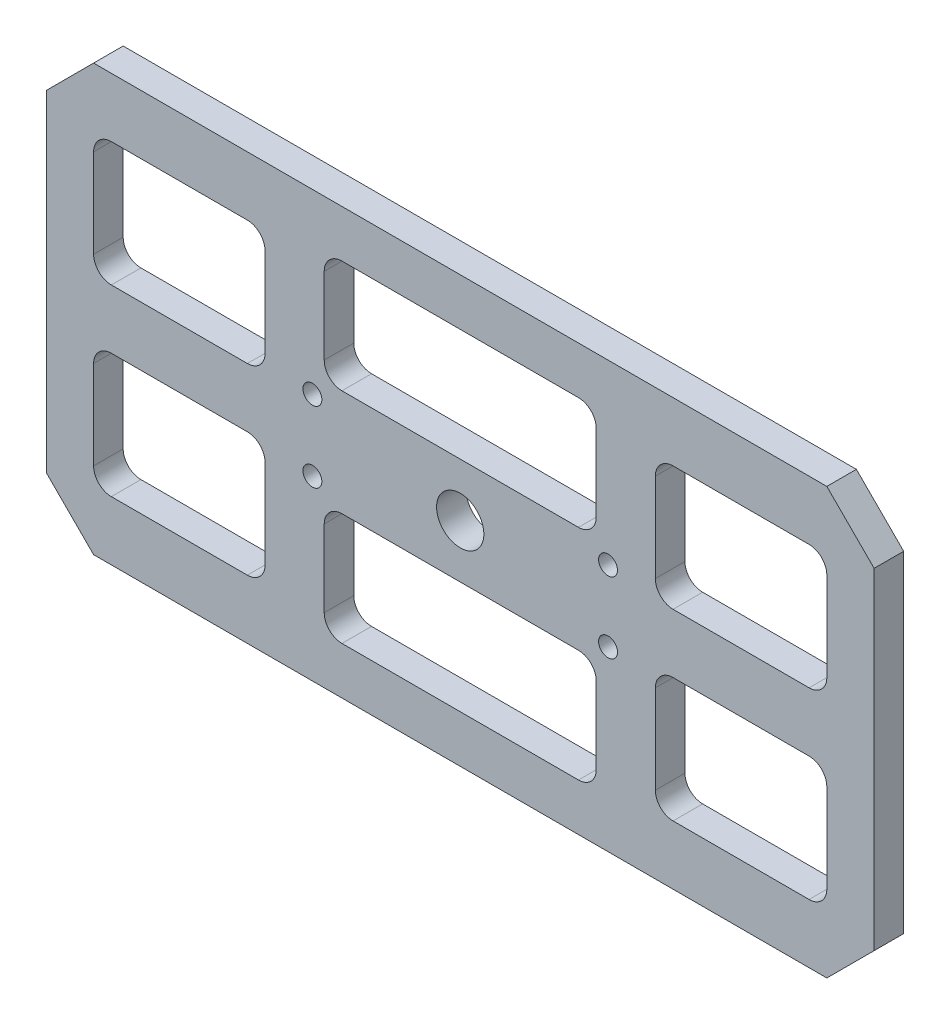
SolidWorks part; units mm, degrees
material "聚亚安酯(11671)"
ref_plane "前视基准面" through (0, 0, 0) normal (0, 0, 1) x (1, 0, 0)
ref_plane "上视基准面" through (0, 0, 0) normal (0, 1, 0) x (1, 0, 0)
ref_plane "右视基准面" through (0, 0, 0) normal (1, 0, 0) x (0, 0, -1)
sketch "草图1" plane through (0, 0, 0) normal (0, 0, 1) x (1, 0, 0)
  line L0 (0, 25.9347) -> (0, -32.8628) construction
  line L1 (-58.6564, 0) -> (66.0734, 0) construction
  line L3 (-70, 36) -> (70, 36)
  line L4 (-70, 36) -> (-70, -36)
  line L5 (-70, -36) -> (70, -36)
  line L6 (70, 36) -> (70, -36)
  circle A0 centre (-25, 6) radius 1.6
  circle A1 centre (25, 6) radius 1.6
  circle A2 centre (-25, -6) radius 1.6
  circle A3 centre (25, -6) radius 1.6
  circle A4 centre (0, 0) radius 4
  dimension "D1" = 12
  dimension "D2" = 50
  dimension "D3" = 3.2
  dimension "D7" = 8
  dimension "D4" = 30
  dimension "D5" = 30
  dimension "D6" = 70
extrude "凸台-拉伸1" add sketch "草图1" along normal blind 5
sketch "草图2" plane through (0, 0, 5) normal (0, 0, 1) x (1, 0, 0)
  line L0 (0, 60.8083) -> (0, -64.8579) construction
  line L1 (-70, 0) -> (70, 0) construction
  line L2 (-70, 36) -> (-70, -36) construction
  line L3 (-62, 26) -> (-33, 26)
  line L4 (-62, 26) -> (-62, 5)
  line L5 (-62, 5) -> (-33, 5)
  line L6 (-33, 26) -> (-33, 5)
  line L7 (-62, -5) -> (-33, -5)
  line L8 (-62, -5) -> (-62, -26)
  line L9 (-62, -26) -> (-33, -26)
  line L10 (-33, -5) -> (-33, -26)
  line L11 (70, 36) -> (-70, 36) construction
  line L12 (62, -26) -> (33, -26)
  line L13 (33, -5) -> (33, -26)
  line L14 (62, -5) -> (33, -5)
  line L15 (62, -5) -> (62, -26)
  line L16 (62, 5) -> (33, 5)
  line L17 (33, 26) -> (33, 5)
  line L18 (62, 26) -> (33, 26)
  line L19 (62, 26) -> (62, 5)
  line L20 (70, -36) -> (70, 36) construction
  line L21 (-70, -36) -> (70, -36) construction
  line L22 (-23, 28) -> (23, 28)
  line L23 (-23, 28) -> (-23, 9)
  line L24 (-23, 9) -> (23, 9)
  line L25 (23, 28) -> (23, 9)
  line L26 (-23, 28) -> (23, 9) construction
  line L27 (-23, 9) -> (23, 28) construction
  line L28 (-23, -9) -> (23, -9)
  line L29 (-23, -9) -> (-23, -28)
  line L30 (-23, -28) -> (23, -28)
  line L31 (23, -9) -> (23, -28)
  line L32 (-23, -9) -> (23, -28) construction
  line L33 (-23, -28) -> (23, -9) construction
  circle A0 centre (-25, 6) radius 1.6 construction
  circle A1 centre (25, -6) radius 1.6 construction
  circle A2 centre (25, 6) radius 1.6 construction
  point P13 (0, 18.5)
  point P34 (0, -18.5)
  dimension "D1" = 10
  dimension "D2" = 8
  dimension "D3" = 8
  dimension "D4" = 10
  dimension "D5" = 3
  dimension "D6" = 8
  dimension "D7" = 8
  dimension "D8" = 3
  dimension "D9" = 10
extrude "切除-拉伸1" cut sketch "草图2" against normal through all
fillet "圆角1" radius 3 24 edges at (-33, -26, 2.5) (-62, -26, 2.5) (-62, -5, 2.5) (-33, -5, 2.5) (-33, 5, 2.5) (-62, 5, 2.5) (-62, 26, 2.5) (-33, 26, 2.5) (33, 5, 2.5) (33, 26, 2.5) (62, 26, 2.5) (62, 5, 2.5) (62, -26, 2.5) (62, -5, 2.5) (33, -5, 2.5) (33, -26, 2.5) (23, -28, 2.5) (23, -9, 2.5) (-23, -28, 2.5) (-23, -9, 2.5) (23, 28, 2.5) (23, 9, 2.5) (-23, 9, 2.5) (-23, 28, 2.5)
chamfer "倒角1" distance 8 angle 45 4 edges at (70, 36, 2.5) (70, -36, 2.5) (-70, -36, 2.5) (-70, 36, 2.5)
